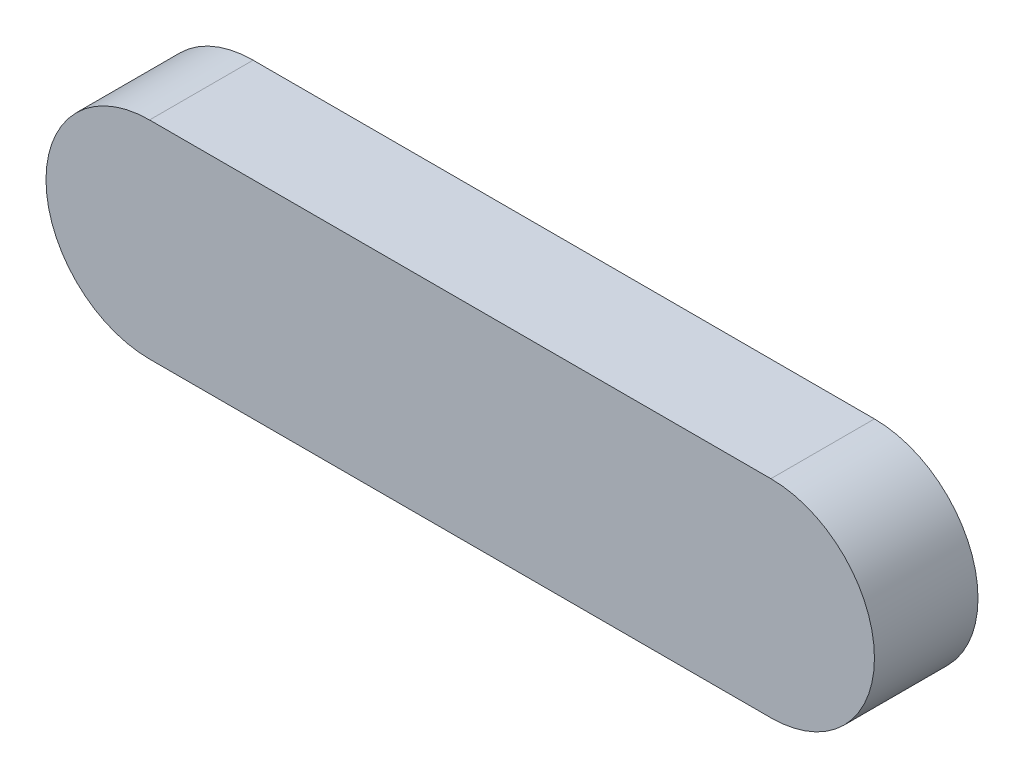
SolidWorks part; units mm, degrees
ref_plane "前视基准面" through (0, 0, 0) normal (0, 0, 1) x (1, 0, 0)
ref_plane "上视基准面" through (0, 0, 0) normal (0, 1, 0) x (1, 0, 0)
ref_plane "右视基准面" through (0, 0, 0) normal (1, 0, 0) x (0, 0, -1)
sketch "草图1" plane through (0, 0, 0) normal (0, 0, 1) x (1, 0, 0)
  line L0 (0, 0) -> (60, 0) construction
  line L1 (0, 10) -> (60, 10)
  line L2 (0, -10) -> (60, -10)
  arc A0 (0, 10) -> (0, -10) centre (0, 0) ccw
  arc A1 (60, -10) -> (60, 10) centre (60, 0) ccw
  point P3 (30, 0)
  dimension "D1" = 60
  dimension "D2" = 20
extrude "凸台-拉伸1" add sketch "草图1" along normal blind 10
